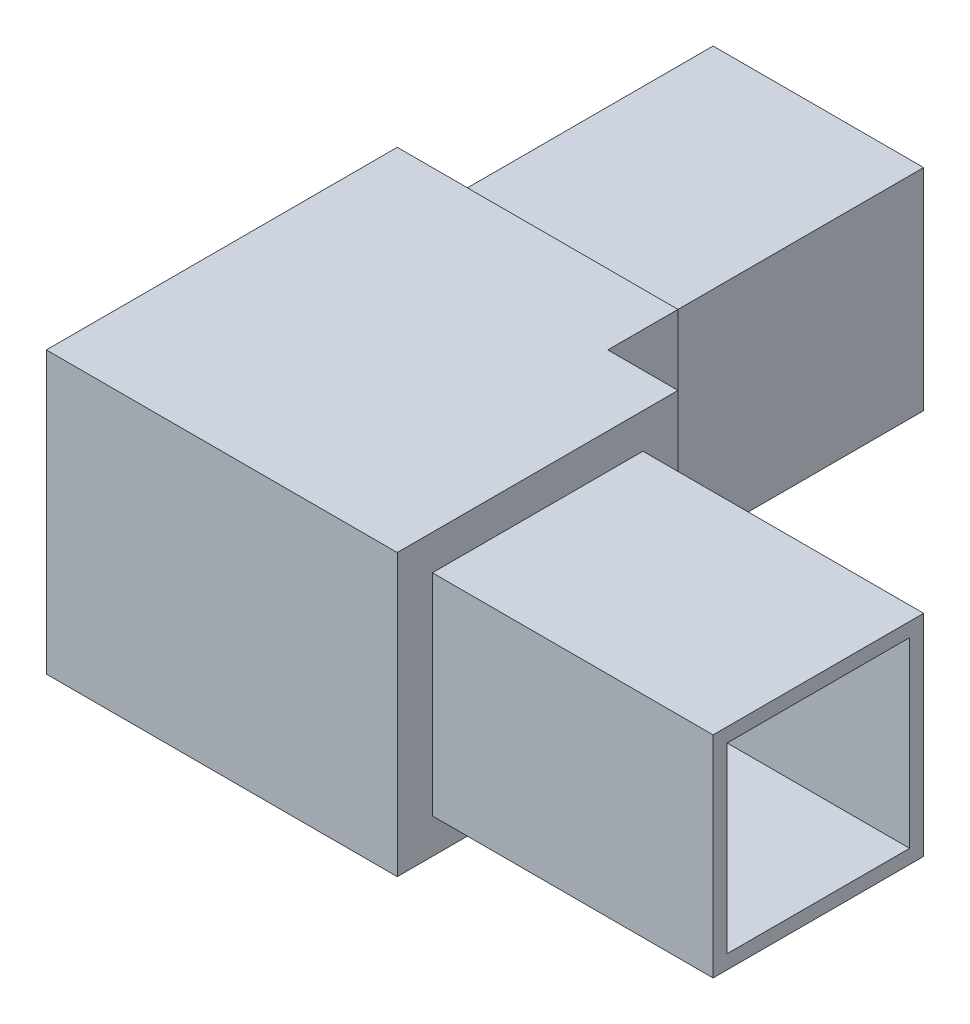
SolidWorks part; units mm, degrees
ref_plane "Alzado" through (0, 0, 0) normal (0, 0, 1) x (1, 0, 0)
ref_plane "Planta" through (0, 0, 0) normal (0, 1, 0) x (1, 0, 0)
ref_plane "Vista lateral" through (0, 0, 0) normal (1, 0, 0) x (0, 0, -1)
sketch "Croquis1" plane through (0, 0, 0) normal (0, 1, 0) x (1, 0, 0)
  line L1 (20, -20) -> (-20, -20)
  line L2 (20, -20) -> (20, 20)
  line L3 (20, 20) -> (-20, 20)
  line L4 (-20, -20) -> (-20, 20)
  line L5 (20, -20) -> (-20, 20) construction
  line L6 (20, 20) -> (-20, -20) construction
  line L7 (20, -20) -> (70, -20)
  line L8 (20, -20) -> (20, 20)
  line L9 (20, 20) -> (70, 20)
  line L10 (70, -20) -> (70, 20)
  line L11 (-20, 20) -> (20, 20)
  line L12 (-20, 20) -> (-20, 70)
  line L13 (-20, 70) -> (20, 70)
  line L14 (20, 20) -> (20, 70)
  point P0 (0, 0)
  dimension "D1" = 40
  dimension "D2" = 40
  dimension "D3" = 50
  dimension "D4" = 50
extrude "Extruir1" add sketch "Croquis1" along normal blind 40 contours L3 L14 L13 L12 | L4 L1 L2 L3 | L7 L10 L9 L2
sketch "Croquis2" plane through (70, 0, 0) normal (1, 0, 0) x (0, 0, -1)
  line L4 (-20, 0) -> (20, 0)
  line L5 (20, 0) -> (20, 40)
  line L6 (20, 40) -> (-20, 40)
  line L7 (-20, 40) -> (-20, 0)
  line L8 (-20, 0) -> (20, 0)
  line L9 (20, 0) -> (20, 40)
  line L10 (20, 40) -> (-20, 40)
  line L11 (-20, 40) -> (-20, 0)
  line L16 (-15, 5) -> (15, 5)
  line L17 (15, 5) -> (15, 35)
  line L18 (15, 35) -> (-15, 35)
  line L19 (-15, 35) -> (-15, 5)
  line L20 (-15, 5) -> (15, 5)
  line L21 (15, 5) -> (15, 35)
  line L22 (15, 35) -> (-15, 35)
  line L23 (-15, 35) -> (-15, 5)
  dimension "D1" = 0
  dimension "D2" = 5
extrude "Extruir2" cut sketch "Croquis2" against normal blind 40
sketch "Croquis3" plane through (0, 0, -70) normal (0, 0, -1) x (-1, 0, 0)
  line L0 (-15, 5) -> (15, 5)
  line L1 (15, 5) -> (15, 35)
  line L2 (15, 35) -> (-15, 35)
  line L3 (-15, 35) -> (-15, 5)
  line L4 (-20, 0) -> (20, 0)
  line L5 (20, 0) -> (20, 40)
  line L6 (20, 40) -> (-20, 40)
  line L7 (-20, 40) -> (-20, 0)
  line L8 (-20, 0) -> (20, 0)
  line L9 (20, 0) -> (20, 40)
  line L10 (20, 40) -> (-20, 40)
  line L11 (-20, 40) -> (-20, 0)
  dimension "D1" = 0
  dimension "D2" = 5
extrude "Extruir3" cut sketch "Croquis3" against normal blind 40
shell "Vaciado1" thickness 2
sketch "Croquis4" plane through (-20, 0, 0) normal (-1, 0, 0) x (0, 0, 1)
  line L0 (0, 20) -> (20, 20) construction
  line L4 (20, 40) -> (20, 0) construction
  circle A0 centre (0, 20) radius 10
  dimension "D1" = 20
  dimension "D2" = 20
extrude "Cortar-Extruir1" cut sketch "Croquis4" against normal blind 10
